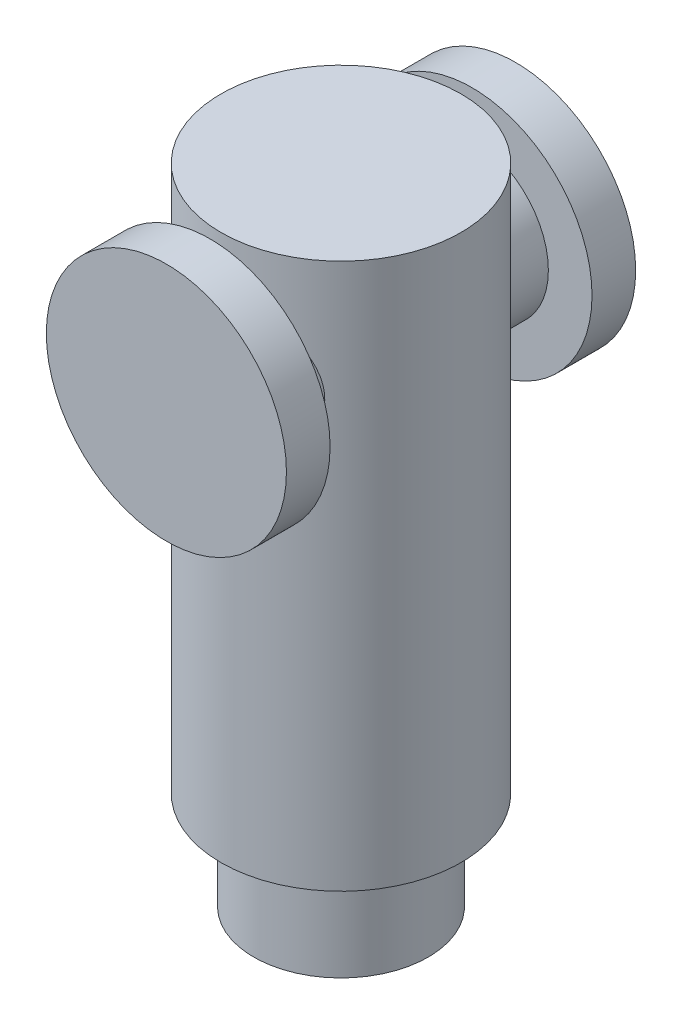
SolidWorks part; units mm, degrees
ref_plane "Front Plane" through (0, 0, 0) normal (0, 0, 1) x (1, 0, 0)
ref_plane "Top Plane" through (0, 0, 0) normal (0, 1, 0) x (1, 0, 0)
ref_plane "Right Plane" through (0, 0, 0) normal (1, 0, 0) x (0, 0, -1)
sketch "Sketch1" plane through (0, 0, 0) normal (0, 0, 1) x (1, 0, 0)
  circle A0 centre (0, 0) radius 34.925
extrude "Boss-Extrude1" add sketch "Sketch1" along normal blind 12.7
sketch "Sketch2" plane through (0, 0, 12.7) normal (0, 0, 1) x (1, 0, 0)
  circle A0 centre (0, 0) radius 22.225
extrude "Boss-Extrude2" add sketch "Sketch2" along normal blind 12.7
sketch "Sketch3" plane through (0, 0, 0) normal (0, 1, 0) x (1, 0, 0)
  line L0 (34.925, 0) -> (-34.925, 0) construction
  circle A0 centre (0, -50.8) radius 34.925
  dimension "D1" = 50.8
extrude "Boss-Extrude4" add sketch "Sketch3" along normal blind 34.925 and the other way blind 123.825
pattern_circular "CirPattern1" count 2 every 180 about axis through (0, 0, 0) along (0, 0, 1) of "Boss-Extrude1", "Boss-Extrude2"
pattern_circular "CirPattern2" count 2 every 180 about axis through (0, 34.925, 50.8) along (0, 1, 0) of "Boss-Extrude1"
sketch "Sketch5" plane through (0, -123.825, 0) normal (0, -1, 0) x (1, 0, 0)
  circle A0 centre (0, 50.8) radius 25.4
extrude "Boss-Extrude5" add sketch "Sketch5" along normal blind 28.575
